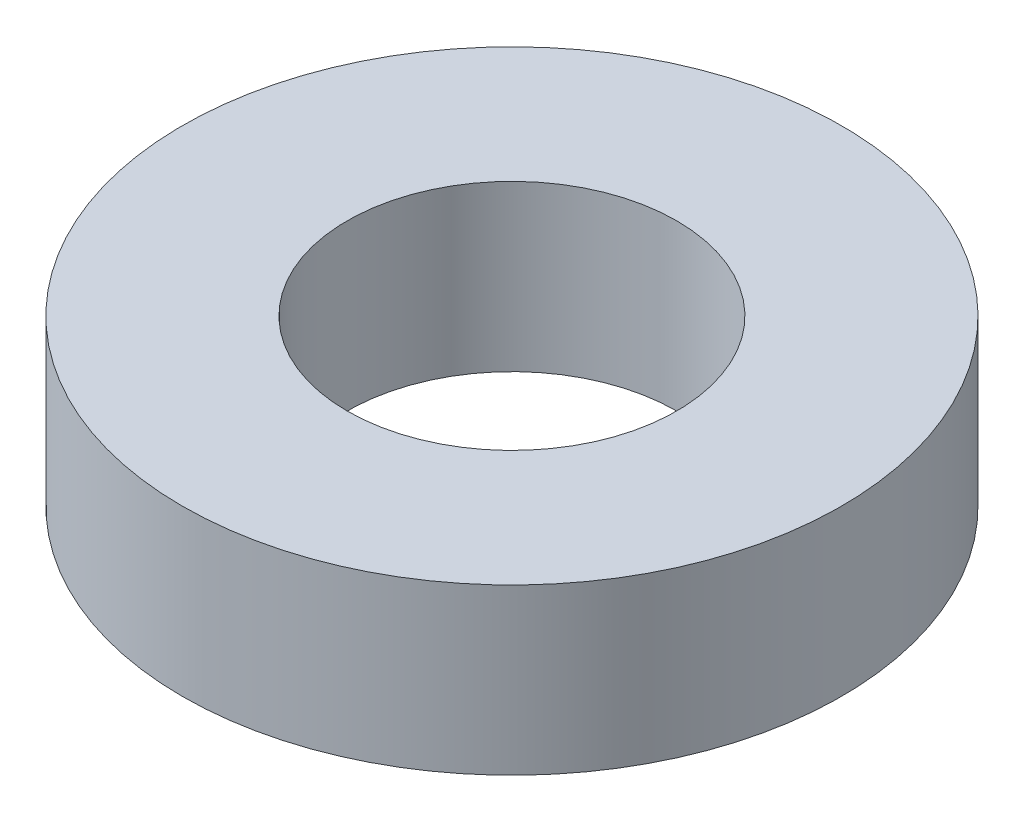
SolidWorks part; units mm, degrees
ref_plane "Front Plane" through (0, 0, 0) normal (0, 0, 1) x (1, 0, 0)
ref_plane "Top Plane" through (0, 0, 0) normal (0, 1, 0) x (1, 0, 0)
ref_plane "Right Plane" through (0, 0, 0) normal (1, 0, 0) x (0, 0, -1)
sketch "Sketch1" plane through (0, 0, 0) normal (0, 1, 0) x (1, 0, 0)
  circle A0 centre (0, 0) radius 12.7
  circle A1 centre (0, 0) radius 6.35
  dimension "D1" = 12.7
  dimension "D2" = 25.4
extrude "Boss-Extrude1" add sketch "Sketch1" along normal blind 6.35
